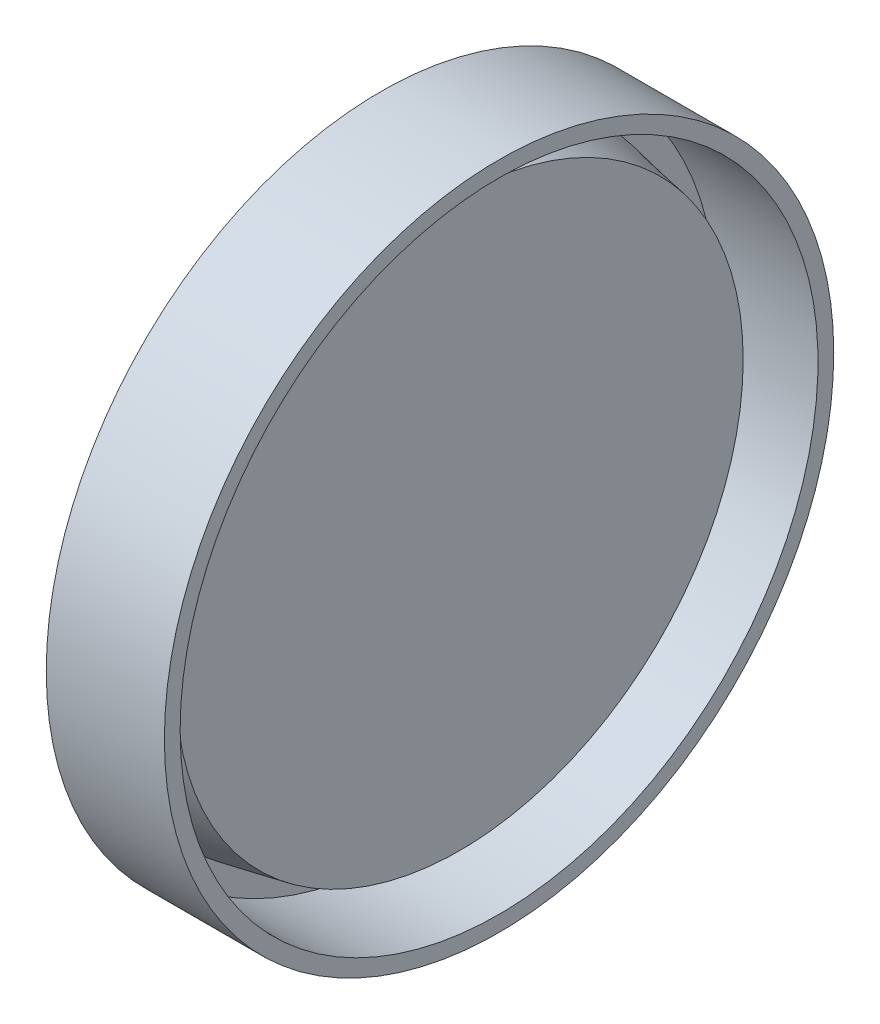
SolidWorks part; units mm, degrees
ref_plane "Front Plane" through (0, 0, 0) normal (0, 0, 1) x (1, 0, 0)
ref_plane "Top Plane" through (0, 0, 0) normal (0, 1, 0) x (1, 0, 0)
ref_plane "Right Plane" through (0, 0, 0) normal (1, 0, 0) x (0, 0, -1)
sketch "Sketch1" plane through (0, 0, 0) normal (0, 0, 1) x (1, 0, 0)
  line L0 (0, 0) -> (28.55, 0) construction
  line L1 (0, 0) -> (0, 34.3401)
  line L2 (0, 34.3401) -> (-8, 35.8401)
  line L3 (-8, 35.8401) -> (-8, 42.5)
  line L4 (-8, 42.5) -> (7, 42.5)
  line L5 (7, 42.5) -> (7, 40.5)
  line L6 (7, 40.5) -> (-6, 40.5)
  line L7 (-6, 40.5) -> (-6, 37.5)
  line L8 (-6, 37.5) -> (2, 36)
  line L9 (2, 36) -> (2, 0)
  line L10 (2, 0) -> (0, 0)
  line L11 (-4, 35.0901) -> (-3.6314, 37.0559) construction
  line L12 (-6, 39) -> (-8, 39) construction
  point P5 (2, 22.3059)
  point P16 (2, 29.7977)
  dimension "D1" = 2
  dimension "D2" = 81
  dimension "D3" = 3
  dimension "D4" = 72
  dimension "D5" = 10
  dimension "D6" = 15
revolve "Revolve1" add sketch "Sketch1" angle 360 about L0
